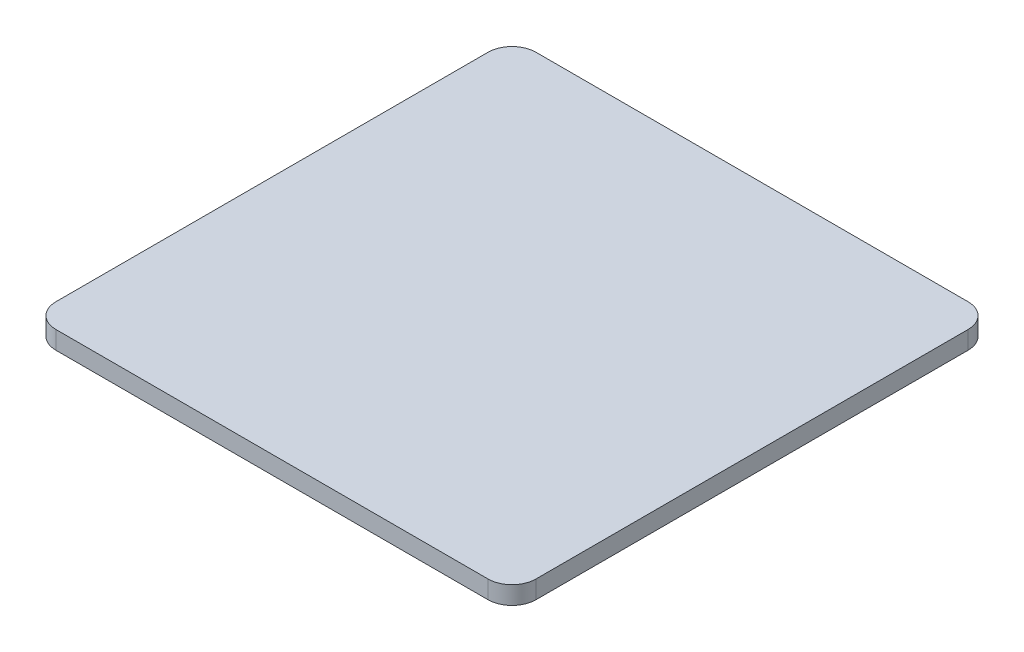
SolidWorks part; units mm, degrees
ref_plane "Front Plane" through (0, 0, 0) normal (0, 0, 1) x (1, 0, 0)
ref_plane "Top Plane" through (0, 0, 0) normal (0, 1, 0) x (1, 0, 0)
ref_plane "Right Plane" through (0, 0, 0) normal (1, 0, 0) x (0, 0, -1)
sketch "Sketch1" plane through (0, 0, 0) normal (0, 1, 0) x (1, 0, 0)
  line L1 (-40, 40) -> (40, 40)
  line L2 (-40, 40) -> (-40, -40)
  line L3 (-40, -40) -> (40, -40)
  line L4 (40, 40) -> (40, -40)
  line L5 (-40, 40) -> (40, -40) construction
  line L6 (-40, -40) -> (40, 40) construction
  point P0 (0, 0)
  dimension "D1" = 80
  dimension "D2" = 80
extrude "Boss-Extrude1" add sketch "Sketch1" along normal blind 3
fillet "Fillet1" radius 4 4 edges at (-40, 1.5, -40) (40, 1.5, -40) (40, 1.5, 40) (-40, 1.5, 40)
